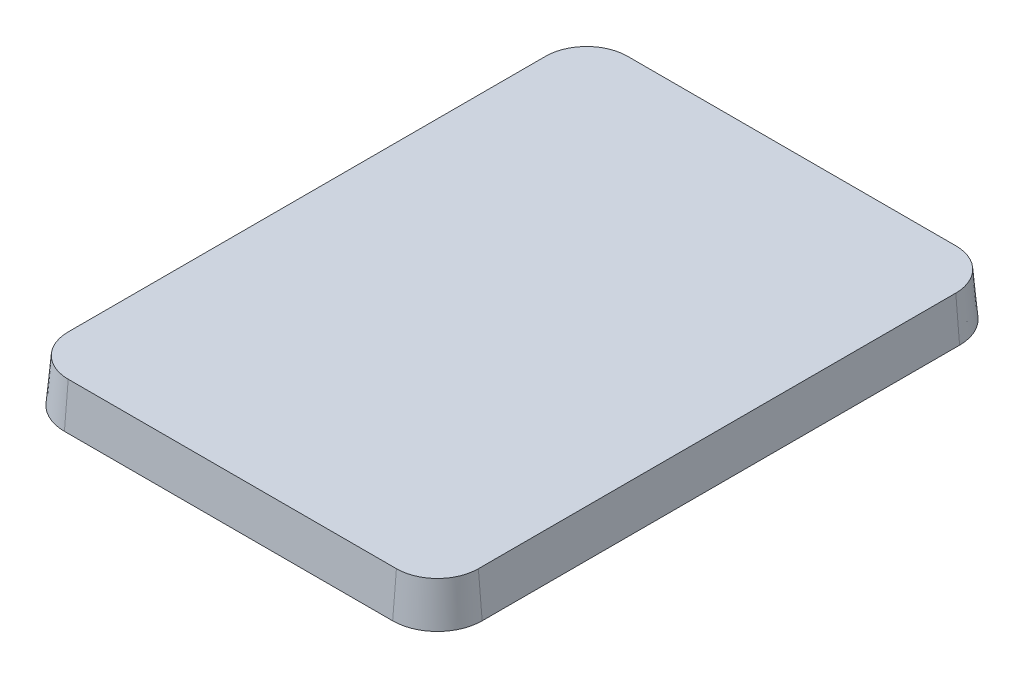
SolidWorks part; units mm, degrees
ref_plane "Front Plane" through (0, 0, 0) normal (0, 0, 1) x (1, 0, 0)
ref_plane "Top Plane" through (0, 0, 0) normal (0, 1, 0) x (1, 0, 0)
ref_plane "Right Plane" through (0, 0, 0) normal (1, 0, 0) x (0, 0, -1)
sketch "Sketch3" plane through (0, 0, 0) normal (0, 1, 0) x (1, 0, 0)
  line L1 (-22, 38) -> (22, 38)
  line L2 (-28, 32) -> (-28, -32)
  line L3 (-22, -38) -> (22, -38)
  line L4 (28, 32) -> (28, -32)
  line L5 (-28, 38) -> (28, -38) construction
  line L6 (-28, -38) -> (28, 38) construction
  arc A0 (22, 38) -> (28, 32) centre (22, 32) cw
  arc A1 (-28, -32) -> (-22, -38) centre (-22, -32) ccw
  arc A2 (-22, 38) -> (-28, 32) centre (-22, 32) ccw
  arc A3 (22, -38) -> (28, -32) centre (22, -32) ccw
  point P0 (0, 0)
  dimension "D3" = 6
  dimension "D1" = 56
  dimension "D2" = 76
extrude "Boss-Extrude2" add sketch "Sketch3" along normal blind 5.8 draft 5
sketch "Sketch4" plane through (0, 5.8, 0) normal (0, 1, 0) x (1, 0, 0)
  line L1 (21, -30) -> (-21, -30)
  line L2 (21, -30) -> (21, 24)
  line L3 (21, 24) -> (-21, 24)
  line L4 (-21, -30) -> (-21, 24)
  line L5 (21, -30) -> (-21, 24) construction
  line L6 (21, 24) -> (-21, -30) construction
  point P0 (0, -3)
  dimension "D1" = 42
  dimension "D2" = 54
  dimension "D3" = 3
